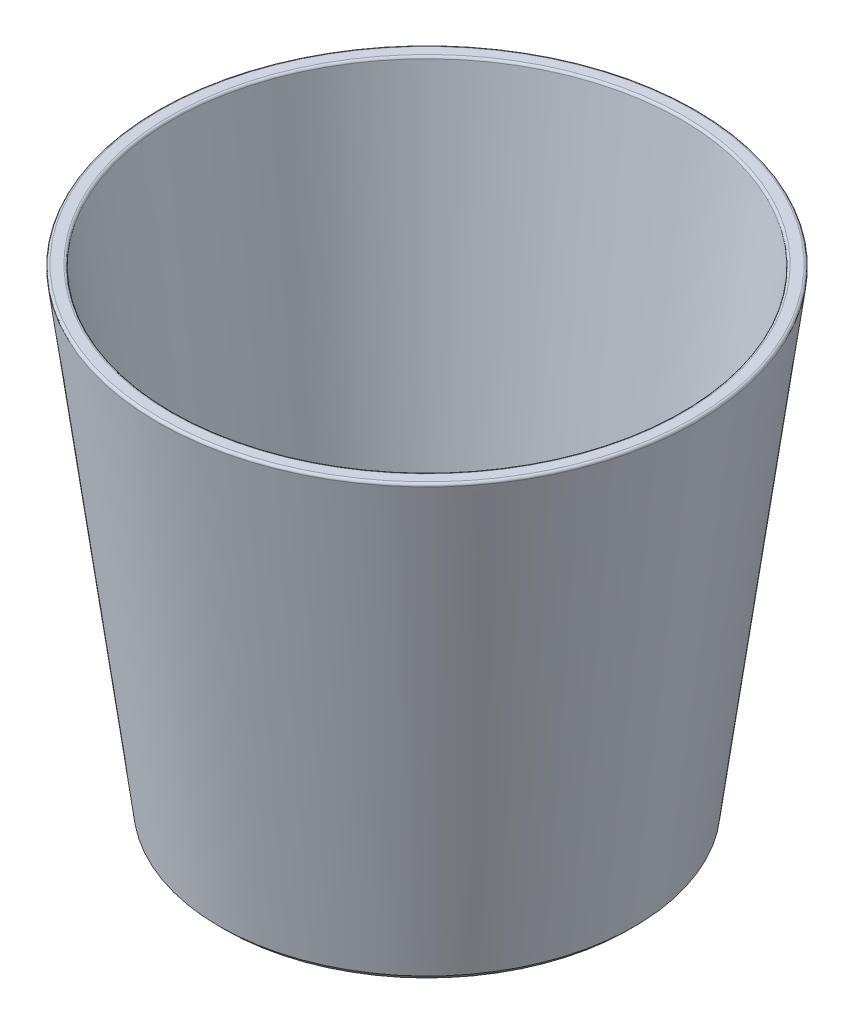
SolidWorks part; units mm, degrees
ref_plane "Front Plane" through (0, 0, 0) normal (0, 0, 1) x (1, 0, 0)
ref_plane "Top Plane" through (0, 0, 0) normal (0, 1, 0) x (1, 0, 0)
ref_plane "Right Plane" through (0, 0, 0) normal (1, 0, 0) x (0, 0, -1)
sketch "Sketch1" plane through (0, 0, 0) normal (1, 0, 0) x (0, 0, -1)
  line L0 (0, 0) -> (52.5, 0) construction
  line L1 (0, 0) -> (0, -95) construction
  line L2 (0, -95) -> (40, -95)
  line L3 (52.5, 0) -> (40, -95)
  line L5 (55.5259, 0) -> (42.6311, -98)
  line L6 (0, -98) -> (42.6311, -98)
  line L8 (0, -95) -> (0, -98)
  line L9 (52.5, 0) -> (55.5259, 0)
  line L10 (0, 3) -> (55.9206, 3) construction
  line L11 (55.9206, 3) -> (42.6311, -98) construction
  dimension "D1" = 52.5
  dimension "D2" = 40
  dimension "D3" = 95
  dimension "D4" = 3
revolve "Revolve1" add sketch "Sketch1" angle 360 about L1
chamfer "Chamfer1" distance 1 angle 45 1 edges at (0, -98, 42.6311)
fillet "Fillet1" radius 0.5 2 edges at (0, 0, 55.5259) (0, 0, 52.5)
